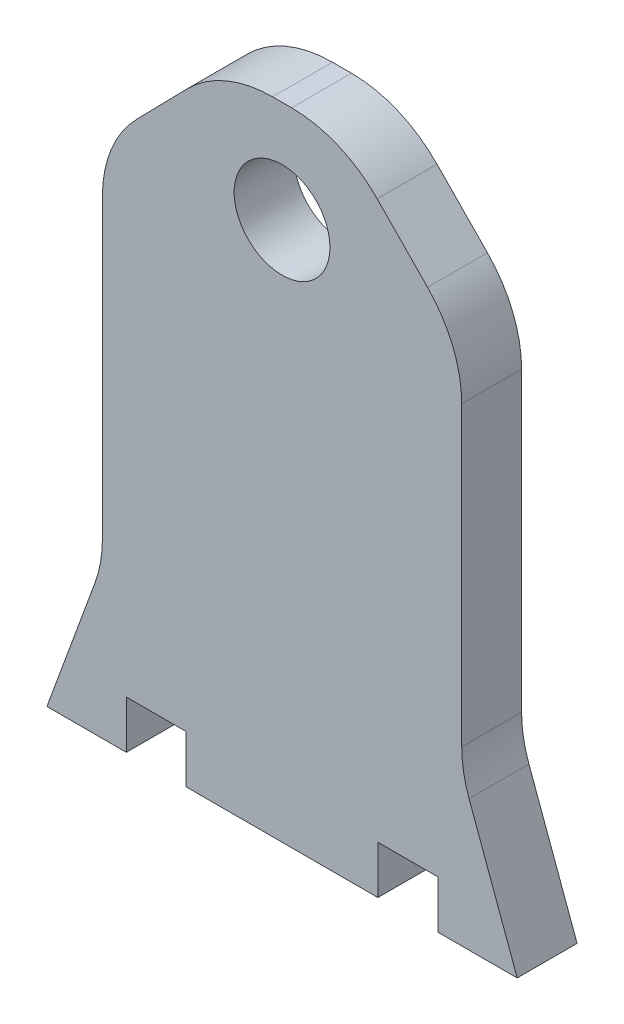
SolidWorks part; units mm, degrees
ref_plane "Plan de face" through (0, 0, 0) normal (0, 0, 1) x (1, 0, 0)
ref_plane "Plan de dessus" through (0, 0, 0) normal (0, 1, 0) x (1, 0, 0)
ref_plane "Plan de droite" through (0, 0, 0) normal (1, 0, 0) x (0, 0, -1)
sketch "Esquisse1" plane through (0, 0, 0) normal (0, 0, 1) x (1, 0, 0)
  line L0 (0, 33.5) -> (0, -8.5) construction
  line L1 (-15, -33.5) -> (15, -33.5)
  line L2 (-15, -33.5) -> (-15, 33.5)
  line L3 (-15, 33.5) -> (15, 33.5)
  line L4 (15, -33.5) -> (15, 33.5)
  line L5 (-15, -33.5) -> (15, 33.5) construction
  line L6 (-15, 33.5) -> (15, -33.5) construction
  circle A1 centre (0, 12.5) radius 4
  point P0 (0, 0)
  dimension "D3" = 42
  dimension "D4" = 8
  dimension "D1" = 67
  dimension "D2" = 30
extrude "Boss.-Extru.1" add sketch "Esquisse1" along normal blind 5
sketch "Esquisse2" plane through (0, 0, 5) normal (0, 0, 1) x (1, 0, 0)
  line L0 (15, -33.5) -> (15, 33.5) construction
  line L1 (-15, 33.5) -> (15, 33.5)
  line L2 (-15, 33.5) -> (-15, 21)
  line L3 (-15, 21) -> (15, 21)
  line L4 (15, 33.5) -> (15, 21)
  dimension "D1" = 12.5
extrude "Enlèv. mat.-Extru.1" cut sketch "Esquisse2" against normal blind 5
sketch "Esquisse3" plane through (0, 0, 5) normal (0, 0, 1) x (1, 0, 0)
  line L0 (0, -33.5) -> (8, -33.5) construction
  line L1 (-15, -33.5) -> (15, -33.5) construction
  line L2 (8, -33.5) -> (13, -33.5) construction
  line L3 (0, -33.5) -> (-8, -33.5) construction
  line L4 (-8, -33.5) -> (-13, -33.5) construction
  line L6 (-13, -33.5) -> (-8, -33.5)
  line L7 (-13, -33.5) -> (-13, -28.5)
  line L8 (-13, -28.5) -> (-8, -28.5)
  line L9 (-8, -33.5) -> (-8, -28.5)
  line L10 (8, -33.5) -> (13, -33.5)
  line L11 (8, -33.5) -> (8, -28.5)
  line L12 (8, -28.5) -> (13, -28.5)
  line L13 (13, -33.5) -> (13, -28.5)
  dimension "D1" = 8
  dimension "D2" = 5
  dimension "D3" = 8
  dimension "D4" = 5
  dimension "D5" = 5
  dimension "D6" = 5
extrude "Enlèv. mat.-Extru.2" cut sketch "Esquisse3" against normal through all
sketch "Esquisse5" plane through (0, 0, 5) normal (0, 0, 1) x (1, 0, 0)
  line L0 (-15, -6.25) -> (-15, -33.5) construction
  line L1 (-15, 21) -> (-15, -33.5) construction
  line L2 (-15, -19.875) -> (-20, -33.5)
  line L3 (15, -33.5) -> (15, -6.25) construction
  line L4 (15, -33.5) -> (15, 21) construction
  line L5 (-20, -33.5) -> (-15, -33.5)
  line L6 (15, -19.875) -> (20, -33.5)
  line L7 (20, -33.5) -> (15, -33.5)
  line L8 (-15, -19.875) -> (-15, -33.5)
  line L9 (15, -33.5) -> (15, -19.875)
  dimension "D1" = 5
  dimension "D2" = 5
extrude "Boss.-Extru.2" add sketch "Esquisse5" against normal blind 5
sketch "Esquisse6" plane through (0, 0, 5) normal (0, 0, 1) x (1, 0, 0)
  line L0 (-15, 21) -> (-15, 0.5625) construction
  line L1 (-15, 21) -> (-15, -19.875) construction
  line L2 (15, 0.5625) -> (15, 21) construction
  line L3 (15, -19.875) -> (15, 21) construction
  line L4 (-15, 10.7813) -> (-5, 21)
  line L5 (-5, 21) -> (-15, 21)
  line L6 (-15, 21) -> (-15, 10.7813)
  line L7 (15, 10.7813) -> (5, 21)
  line L8 (-15, 21) -> (15, 21) construction
  line L9 (5, 21) -> (15, 21)
  line L10 (15, 21) -> (15, 10.7813)
  dimension "D1" = 10
  dimension "D2" = 10
extrude "Enlèv. mat.-Extru.3" cut sketch "Esquisse6" against normal through all
sketch "Esquisse8" plane through (0, 0, 5) normal (0, 0, 1) x (1, 0, 0)
  line L1 (-20, -33.5) -> (21.1134, -33.5)
  line L2 (-20, -33.5) -> (-20, -32.5)
  line L3 (-20, -32.5) -> (21.1134, -32.5)
  line L4 (21.1134, -33.5) -> (21.1134, -32.5)
  dimension "D1" = 1
extrude "Enlèv. mat.-Extru.4" cut sketch "Esquisse8" against normal through all
fillet "Congé1" radius 10 4 edges at (15, 10.7813, 2.5) (-15, 10.7813, 2.5) (5, 21, 2.5) (-5, 21, 2.5)
fillet "Congé2" radius 10 2 edges at (-15, -19.875, 2.5) (15, -19.875, 2.5)
